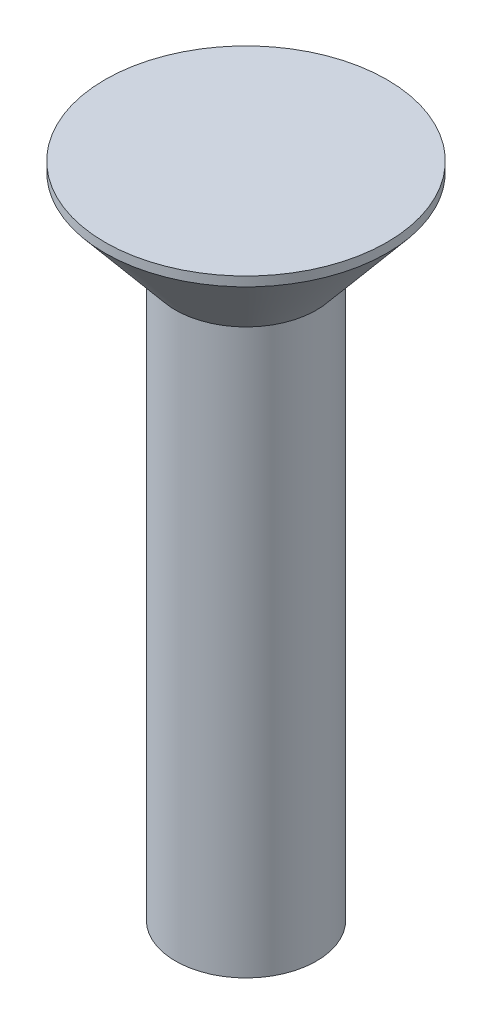
SolidWorks part; units mm, degrees
material "AISI 304"
ref_plane "前视基准面" through (0, 0, 0) normal (0, 0, 1) x (1, 0, 0)
ref_plane "上视基准面" through (0, 0, 0) normal (0, 1, 0) x (1, 0, 0)
ref_plane "右视基准面" through (0, 0, 0) normal (1, 0, 0) x (0, 0, -1)
sketch "草图2" plane through (0, 0, 0) normal (0, 0, 1) x (1, 0, 0)
  line L0 (0, 0) -> (3, 0)
  line L1 (3, 0) -> (3, -0.2)
  line L2 (3, -0.2) -> (1.5, -2)
  line L3 (1.5, -2) -> (1.5, -14)
  line L4 (1.5, -14) -> (0, -14)
  line L5 (0, -14) -> (0, 0)
  dimension "D1" = 3
  dimension "D2" = 0.2
  dimension "D3" = 12
  dimension "D4" = 2
  dimension "D5" = 1.5
revolve "旋转1" add sketch "草图2" angle 360 about L5
